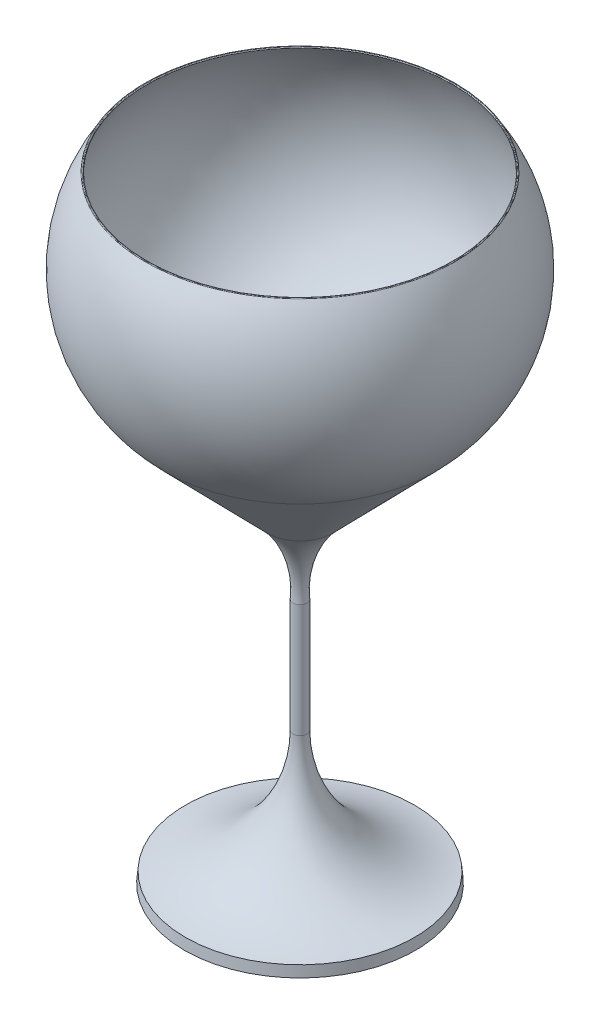
SolidWorks part; units mm, degrees
ref_plane "Front Plane" through (0, 0, 0) normal (0, 0, 1) x (1, 0, 0)
ref_plane "Top Plane" through (0, 0, 0) normal (0, 1, 0) x (1, 0, 0)
ref_plane "Right Plane" through (0, 0, 0) normal (1, 0, 0) x (0, 0, -1)
sketch "Sketch2" plane through (0, 0, 0) normal (0, 0, 1) x (1, 0, 0)
  line L0 (0, 0) -> (0, 204) construction
  line L1 (20.5913, 0) -> (37.5, 0)
  line L2 (37.5, 0) -> (37.1938, 3.5)
  line L3 (2.25, 43.1791) -> (2.25, 80)
  line L4 (10.6971, 103.8773) -> (43.9485, 137.772)
  line L5 (40.3344, 135.1589) -> (10.4109, 104.6566)
  line L6 (49.9094, 200) -> (50.0931, 200)
  line L8 (20.5913, 0) -> (0, 0)
  arc A0 (18.7193, 0.3636) -> (0, 4) centre (0, -46) ccw
  arc A1 (18.7193, 0.3636) -> (20.5913, 0) centre (20.5913, 5) ccw
  arc A2 (37.1938, 3.5) -> (2.25, 43.1791) centre (42.25, 43.1791) cw
  arc A3 (2.25, 80) -> (10.6971, 103.8773) centre (32.1126, 82.8683) cw
  arc A4 (50.2611, 199.9085) -> (43.9485, 137.772) centre (8.256, 172.787) cw
  arc A5 (49.7416, 199.6912) -> (40.3344, 135.1589) centre (8.256, 172.787) cw
  arc A6 (10.4109, 104.6566) -> (6.9264, 103.1588) centre (6.8417, 108.1581) cw
  arc A7 (6.9264, 103.1588) -> (0, 101.672) centre (-59.496, 395.7132) cw
  arc A8 (50.0931, 200) -> (50.2611, 199.9085) centre (50.0931, 199.8) cw
  arc A9 (49.9094, 200) -> (49.7416, 199.6912) centre (49.9094, 199.8) ccw
  point P7 (0, 4)
  point P8 (0, 4)
  point P21 (0, 204)
  point P22 (58, 167.7334)
  dimension "D6" = 100
  dimension "D1" = 5
  dimension "D2" = 40
  dimension "D10" = 30
  dimension "D12" = 50
  dimension "D15" = 64.2251
  dimension "D16" = 5
  dimension "D17" = 300
  dimension "D18" = 0.75
  dimension "D13" = 0.2
  dimension "D19" = 0.2
  dimension "D3" = 3.5
  dimension "D4" = 5
  dimension "D5" = 4.5
  dimension "D7" = 20.5913
  dimension "D8" = 80
  dimension "D9" = 37.1938
  dimension "D11" = 200
  dimension "D14" = 58
  dimension "D20" = 200
revolve "Revolve2" add sketch "Sketch2" angle 360 about L0
